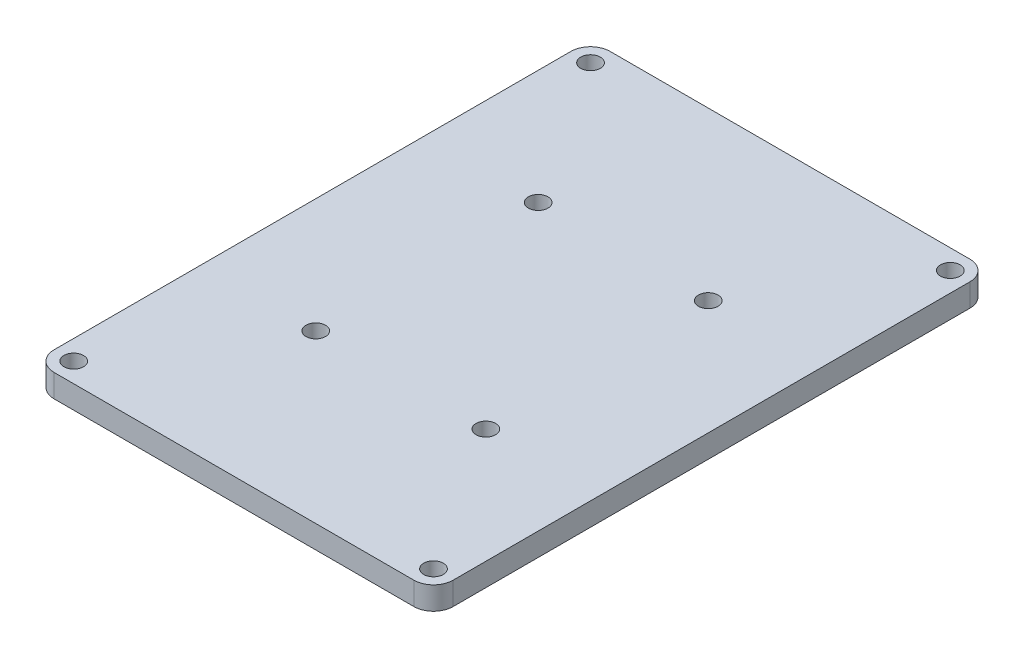
SolidWorks part; units mm, degrees
ref_plane "Front Plane" through (0, 0, 0) normal (0, 0, 1) x (1, 0, 0)
ref_plane "Top Plane" through (0, 0, 0) normal (0, 1, 0) x (1, 0, 0)
ref_plane "Right Plane" through (0, 0, 0) normal (1, 0, 0) x (0, 0, -1)
sketch "Sketch1" plane through (0, 0, 0) normal (0, 1, 0) x (1, 0, 0)
  line L1 (-30.5, 42.5) -> (30.5, 42.5)
  line L2 (-30.5, 42.5) -> (-30.5, -42.5)
  line L3 (-30.5, -42.5) -> (30.5, -42.5)
  line L4 (30.5, 42.5) -> (30.5, -42.5)
  line L5 (-30.5, 42.5) -> (30.5, -42.5) construction
  line L6 (-30.5, -42.5) -> (30.5, 42.5) construction
  point P0 (0, 0)
  dimension "D1" = 61
  dimension "D2" = 85
extrude "Boss-Extrude1" add sketch "Sketch1" along normal blind 3.5
sketch "Sketch2" plane through (0, 3.5, 0) normal (0, 1, 0) x (1, 0, 0)
  line L0 (-30.5, 42.5) -> (-30.5, -42.5) construction
  line L1 (30.5, 42.5) -> (-30.5, 42.5) construction
  line L2 (30.5, -42.5) -> (30.5, 42.5) construction
  line L3 (-30.5, -42.5) -> (30.5, -42.5) construction
  circle A0 centre (-27.5, 39.5) radius 1.5
  circle A1 centre (27.5, 39.5) radius 1.5
  circle A2 centre (-27.5, -39.5) radius 1.5
  circle A3 centre (27.5, -39.5) radius 1.5
  dimension "D1" = 3
  dimension "D3" = 3
  dimension "D4" = 3
  dimension "D2" = 3
extrude "Cut-Extrude1" cut sketch "Sketch2" against normal blind 3.5
sketch "Sketch3" plane through (0, 3.5, 0) normal (0, 1, 0) x (1, 0, 0)
  line L0 (-28.15, 42.5) -> (-28.15, -42.5) construction
  line L1 (30.5, 42.5) -> (-30.5, 42.5) construction
  line L2 (-30.5, -42.5) -> (30.5, -42.5) construction
  line L3 (-30.5, 42.5) -> (-30.5, -42.5) construction
  line L4 (28.15, 42.5) -> (28.15, -42.5) construction
  line L5 (30.5, -42.5) -> (30.5, 42.5) construction
  line L6 (-30.5, 35.5) -> (30.5, 35.5) construction
  line L7 (-30.5, -35.5) -> (30.5, -35.5) construction
  circle A0 centre (-13, 17) radius 1.5
  circle A1 centre (13, -17) radius 1.5
  circle A2 centre (13, 17) radius 1.5
  circle A3 centre (-13, -17) radius 1.5
  dimension "D5" = 17
  dimension "D7" = 13
  dimension "D1" = 2.35
  dimension "D2" = 2.35
  dimension "D3" = 7
  dimension "D4" = 7
  dimension "D6" = 13
  dimension "D8" = 17
extrude "Cut-Extrude2" cut sketch "Sketch3" against normal blind 3.5
fillet "Fillet1" radius 3 4 edges at (-30.5, 1.75, -42.5) (30.5, 1.75, -42.5) (30.5, 1.75, 42.5) (-30.5, 1.75, 42.5)
